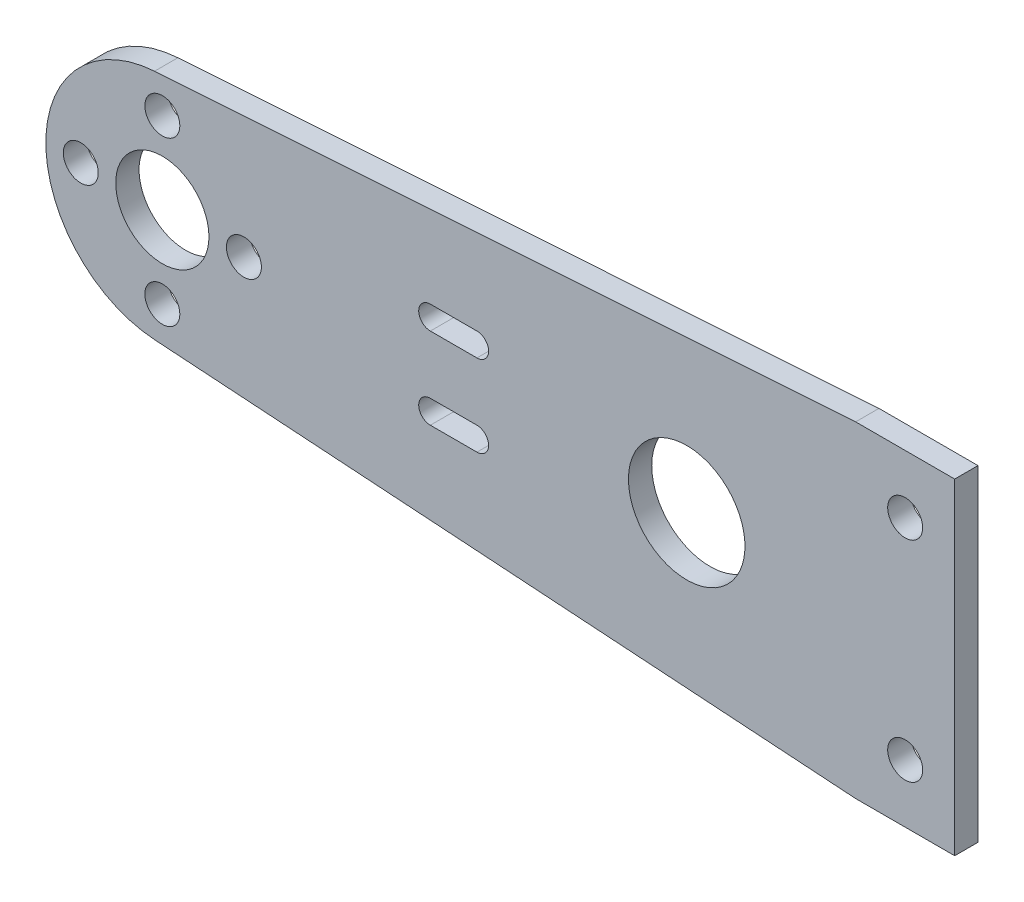
SolidWorks part; units mm, degrees
ref_plane "Спереди" through (0, 0, 0) normal (0, 0, 1) x (1, 0, 0)
ref_plane "Сверху" through (0, 0, 0) normal (0, 1, 0) x (1, 0, 0)
ref_plane "Справа" through (0, 0, 0) normal (1, 0, 0) x (0, 0, -1)
sketch "Sketch1" plane through (0, 0, 0) normal (0, 0, 1) x (1, 0, 0)
  line L4 (0, 0) -> (68, 0) construction
  line L6 (59.5, -14) -> (68, -14)
  line L8 (59.5, 14) -> (68, 14)
  line L9 (68, -14) -> (68, 14)
  line L10 (-0.667, -9.9777) -> (59.5, -14)
  line L11 (-0.667, 9.9777) -> (59.5, 14)
  arc A5 (-0.667, 9.9777) -> (-0.667, -9.9777) centre (0, 0) ccw
  circle A7 centre (0, 0) radius 4
  circle A8 centre (7, 0) radius 1.5
  circle A10 centre (0, -7) radius 1.5
  circle A12 centre (-7, 0) radius 1.5
  circle A14 centre (0, 7) radius 1.5
  circle A16 centre (-4.9497, 4.9497) radius 1.5 [skipped]
  circle A17 centre (-4.9497, -4.9497) radius 1.5 [skipped]
  circle A22 centre (4.9497, 4.9497) radius 1.5 [skipped]
  circle A23 centre (4.9497, -4.9497) radius 1.5 [skipped]
  circle A24 centre (63.75, -9) radius 1.5
  circle A25 centre (63.75, 9) radius 1.5
  point P9 (68, 0)
  point P11 (-10, 0)
  point P22 (63.75, -14)
  point P37 (0, 0)
  dimension "D2" = 78
  dimension "D4" = 28
  dimension "D11" = 10
  dimension "D12" = 8
  dimension "D13" = 7
  dimension "D14" = 3
  dimension "D17" = 5
  dimension "D6" = 3
  dimension "D8" = 3
  dimension "D7" = 10
  dimension "D9" = 5
  dimension "D10" = 68
  dimension "D16" = 7
  dimension "D5" = 8.5
  dimension "D15" = 8
extrude "плата" add sketch "Sketch1" along normal blind 2
sketch "Sketch3" plane through (0, 0, 0) normal (0, 0, -1) x (-1, 0, 0)
  line L0 (-27, -3.5) -> (-23, -3.5) construction
  line L1 (-27, -2.5) -> (-23, -2.5)
  line L2 (-27, -4.5) -> (-23, -4.5)
  line L3 (0, 0) -> (-68, 0) construction
  line L4 (-68, -14) -> (-68, 14) construction
  line L5 (-27, 3.5) -> (-23, 3.5) construction
  line L6 (-27, 2.5) -> (-23, 2.5)
  line L7 (-27, 4.5) -> (-23, 4.5)
  arc A0 (-27, -2.5) -> (-27, -4.5) centre (-27, -3.5) ccw
  arc A1 (-23, -4.5) -> (-23, -2.5) centre (-23, -3.5) ccw
  arc A2 (-27, 2.5) -> (-27, 4.5) centre (-27, 3.5) cw
  arc A3 (-23, 4.5) -> (-23, 2.5) centre (-23, 3.5) cw
  circle A4 centre (-45, 0) radius 5
  point P2 (-25, -3.5)
  point P13 (-68, 0)
  point P15 (-28, -3.5)
  point P16 (-22, -3.5)
  point P21 (-25, 3.5)
  dimension "D1" = 2
  dimension "D5" = 10
  dimension "D2" = 6
  dimension "D3" = 3.5
  dimension "D4" = 25
  dimension "D6" = 45
extrude "Extrude3" cut sketch "Sketch3" against normal through all
sketch "Sketch5" [suppressed] plane through (0, 0, 3) normal (0, 0, 1) x (1, 0, 0)
  line L1 (9.3329, -6) -> (24.323, 0)
  line L2 (5.196, -10.8872) -> (28.3596, -1.6157)
  line L3 (59.3, 14) -> (59.3, 10.7686)
  line L8 (68, -19) -> (68, 19) construction
  line L9 (59.5, -19) -> (68, -19) construction
  line L10 (-1.4776, -9.8902) -> (59.5, -19) construction
  line L11 (68, 0) -> (-10, 0) construction
  line L12 (5.196, 10.8872) -> (28.3596, 1.6157)
  line L13 (59.3, -14) -> (59.3, -10.7686)
  line L14 (9.3329, 6) -> (24.323, 0)
  line L16 (32.3962, 0) -> (59.3, 10.7686)
  line L17 (28.3596, -1.6157) -> (59.3, -14)
  line L18 (32.3962, 0) -> (59.3, -10.7686)
  line L19 (28.3596, 1.6157) -> (59.3, 14)
  line L20 (59.5, 19) -> (-1.4776, 9.8902) construction
  line L22 (9.3329, -6) -> (5.196, -10.8872)
  line L23 (9.3329, 6) -> (5.196, 10.8872)
  arc A1 (-1.4776, 9.8902) -> (-1.4776, -9.8902) centre (0, 0) ccw construction
  circle A2 centre (0, 0) radius 10 construction
  dimension "D6" = 20
  dimension "D3" = 11
  dimension "D1" = 3
  dimension "D2" = 8.7
  dimension "D4" = 5
  dimension "D7" = 12
extrude "Extrude5" [suppressed] add sketch "Sketch5" along normal blind 4
fillet "Fillet2" [suppressed] radius 4
fillet "Fillet3" [suppressed] radius 3
